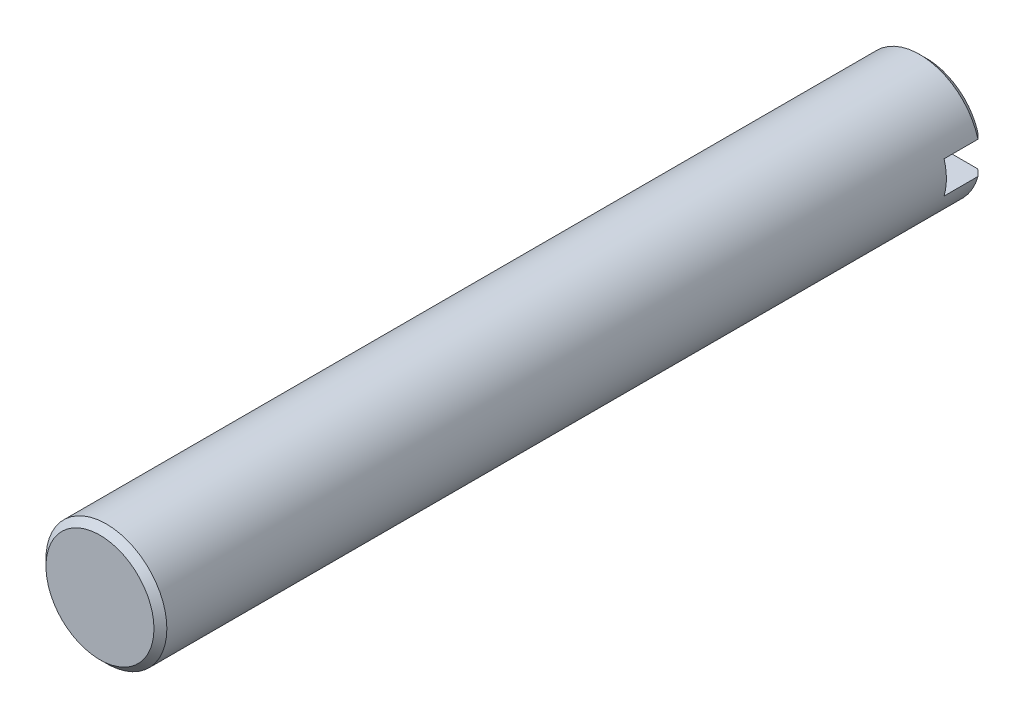
SolidWorks part; units mm, degrees
material "Plain Carbon Steel"
ref_plane "Front Plane" through (0, 0, 0) normal (0, 0, 1) x (1, 0, 0)
ref_plane "Top Plane" through (0, 0, 0) normal (0, 1, 0) x (1, 0, 0)
ref_plane "Right Plane" through (0, 0, 0) normal (1, 0, 0) x (0, 0, -1)
sketch "Sketch1" plane through (0, 0, 0) normal (0, 0, 1) x (1, 0, 0)
  circle A0 centre (-9.3281, 3.2522) radius 4.7625
  dimension "D1" = 9.525
extrude "Boss-Extrude2" add sketch "Sketch1" along normal blind 65.1002
sketch "Sketch4" plane through (0, 0, 0) normal (0, 0, -1) x (-1, 0, 0)
  line L1 (3.8393, 4.5222) -> (14.8169, 4.5222)
  line L2 (3.8393, 4.5222) -> (3.8393, 1.9822)
  line L3 (3.8393, 1.9822) -> (14.8169, 1.9822)
  line L4 (14.8169, 4.5222) -> (14.8169, 1.9822)
  line L5 (3.8393, 4.5222) -> (14.8169, 1.9822) construction
  line L6 (3.8393, 1.9822) -> (14.8169, 4.5222) construction
  point P0 (9.3281, 3.2522)
  dimension "D1" = 2.54
extrude "Cut-Extrude7" cut sketch "Sketch4" against normal blind 3.175
chamfer "Chamfer1" distance 0.508 angle 45 1 edges at (-9.3281, 8.0147, 0)
chamfer "Chamfer2" distance 0.508 angle 45 1 edges at (-9.3281, -1.5103, 0)
chamfer "Chamfer3" distance 0.508 angle 45 1 edges at (-4.5656, 3.2522, 65.1002)
